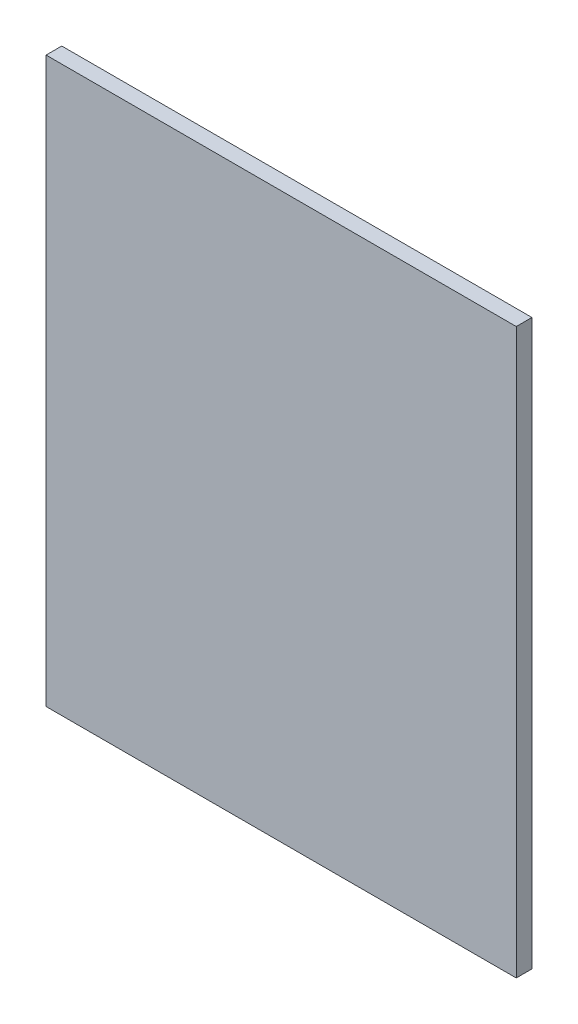
SolidWorks part; units mm, degrees
material "Acrylic (Medium-high impact)"
ref_plane "Front Plane" through (0, 0, 0) normal (0, 0, 1) x (1, 0, 0)
ref_plane "Top Plane" through (0, 0, 0) normal (0, 1, 0) x (1, 0, 0)
ref_plane "Right Plane" through (0, 0, 0) normal (1, 0, 0) x (0, 0, -1)
sketch "Sketch1" plane through (0, 0, 0) normal (0, 0, 1) x (1, 0, 0)
  line L1 (-150, -180) -> (150, -180)
  line L2 (-150, -180) -> (-150, 180)
  line L3 (-150, 180) -> (150, 180)
  line L4 (150, -180) -> (150, 180)
  line L5 (-150, -180) -> (150, 180) construction
  line L6 (-150, 180) -> (150, -180) construction
  point P0 (0, 0)
  dimension "D1" = 300
  dimension "D2" = 360
extrude "Boss-Extrude1" add sketch "Sketch1" along normal blind 10
